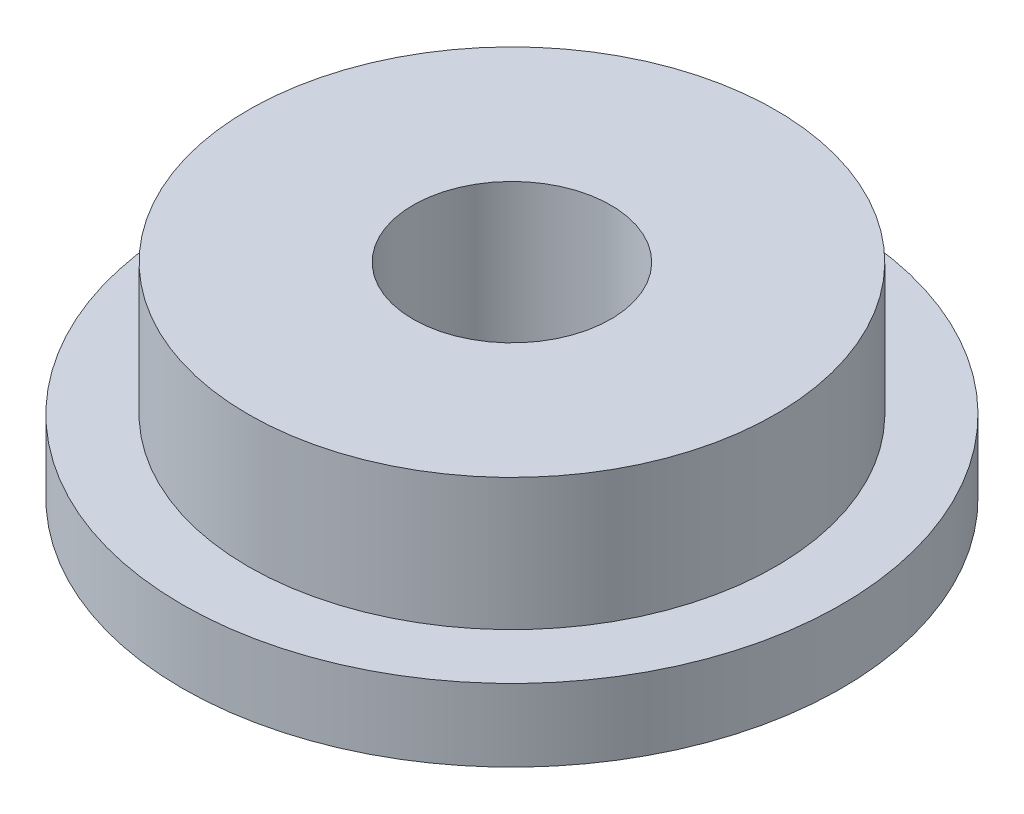
SolidWorks part; units mm, degrees
ref_plane "Front Plane" through (0, 0, 0) normal (0, 0, 1) x (1, 0, 0)
ref_plane "Top Plane" through (0, 0, 0) normal (0, 1, 0) x (1, 0, 0)
ref_plane "Right Plane" through (0, 0, 0) normal (1, 0, 0) x (0, 0, -1)
sketch "Sketch1" plane through (0, 0, 0) normal (0, 1, 0) x (1, 0, 0)
  circle A0 centre (0, 0) radius 5
  dimension "D1" = 10
extrude "Boss-Extrude1" add sketch "Sketch1" along normal blind 1.1
sketch "Sketch3" plane through (0, 1.1, 0) normal (0, 1, 0) x (1, 0, 0)
  circle A0 centre (0, 0) radius 4
  dimension "D1" = 8
extrude "Boss-Extrude2" add sketch "Sketch3" along normal blind 2
sketch "Sketch4" plane through (0, 3.1, 0) normal (0, 1, 0) x (1, 0, 0)
  circle A0 centre (0, 0) radius 1.5
  dimension "D1" = 3
extrude "Cut-Extrude1" cut sketch "Sketch4" against normal through all
